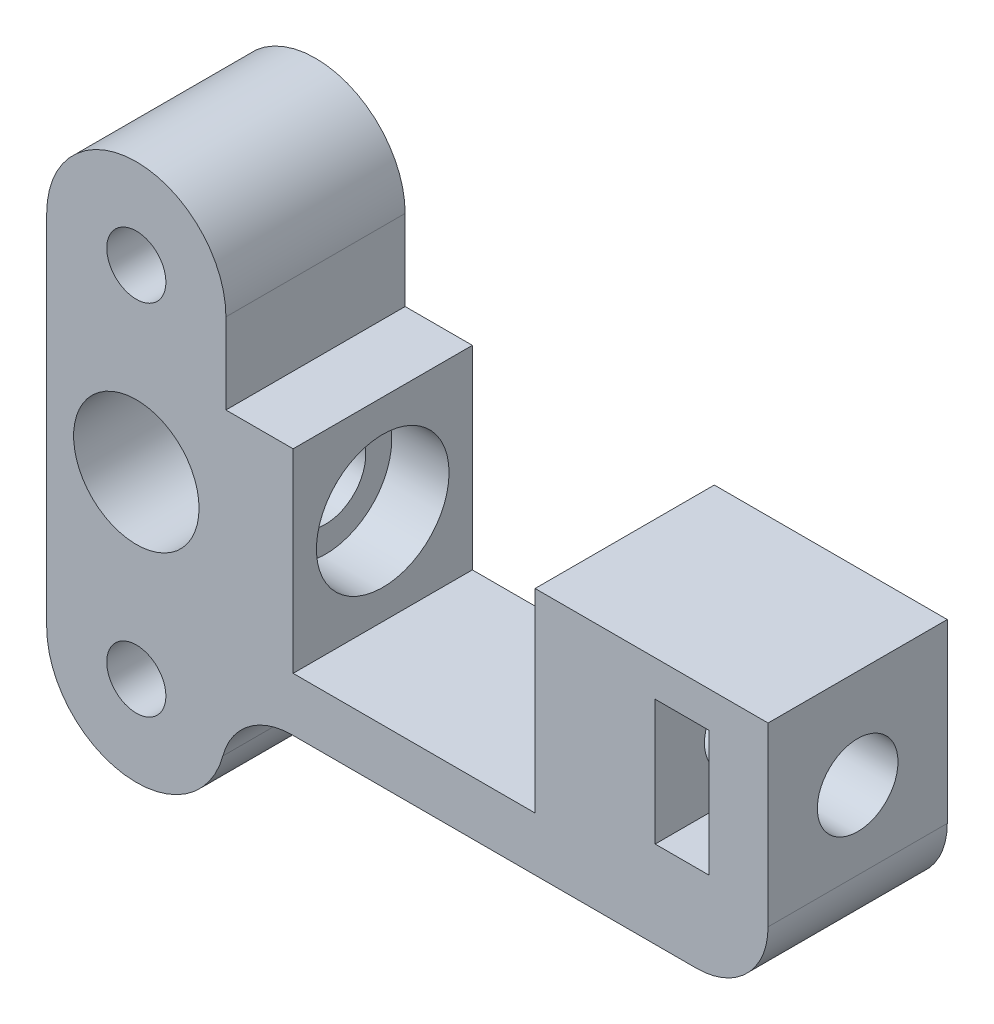
SolidWorks part; units mm, degrees
material "ABS"
ref_plane "Plan de face" through (0, 0, 0) normal (0, 0, 1) x (1, 0, 0)
ref_plane "Plan de dessus" through (0, 0, 0) normal (0, 1, 0) x (1, 0, 0)
ref_plane "Plan de droite" through (0, 0, 0) normal (1, 0, 0) x (0, 0, -1)
sketch "Esquisse1" plane through (0, 0, 0) normal (0, 0, 1) x (1, 0, 0)
  line L0 (0, 0) -> (0, 10) construction
  line L1 (0, 0) -> (0, -10) construction
  line L2 (-5, 10) -> (-5, 2)
  line L3 (-5, 2) -> (-5, -10)
  line L4 (5, 10) -> (5, 0)
  line L5 (5, 0) -> (5, -10)
  circle A0 centre (0, 0) radius 3.5
  circle A1 centre (0, 0) radius 5
  circle A2 centre (0, 10) radius 1.65
  circle A3 centre (0, 10) radius 5
  circle A4 centre (0, -10) radius 1.65
  circle A5 centre (0, -10) radius 5
  point P7 (0, 5)
  point P8 (0, 5)
  dimension "D2" = 3.3
  dimension "D3" = 7
  dimension "D5" = 0
  dimension "D1" = 10
extrude "Shape" add sketch "Esquisse1" along normal blind 10 contours A3 A2 | A3 L2 A1 L4 | A1 A0 | A5 L5 A1 L3 | A5 A4 | A3 A1 L4 | A5 A1 L3
sketch "Esquisse5" plane through (0, 0, 0) normal (0, 0, -1) x (-1, 0, 0)
  circle A0 centre (0, 10) radius 1.65
  circle A1 centre (0, 0) radius 3.5
  circle A2 centre (0, -10) radius 1.65
  circle A3 centre (0, 10) radius 1.65 construction
  circle A4 centre (0, 0) radius 3.5 construction
  circle A5 centre (0, -10) radius 1.65 construction
extrude "HolesCirclesRepeat" [suppressed] cut sketch "Esquisse5" along normal blind 29
sketch "Esquisse6" plane through (5, 0, 0) normal (1, 0, 0) x (0, 0, -1)
  line L0 (0, 0) -> (-10, 0) construction
  line L1 (0, 10) -> (0, -10) construction
  line L2 (-10, 10) -> (-10, -10) construction
  line L4 (0, -7.5) -> (-10, -7.5)
  line L5 (0, -7.5) -> (0, 7.5)
  line L6 (0, 7.5) -> (-10, 7.5)
  line L7 (-10, -7.5) -> (-10, 7.5)
  line L8 (0, -7.5) -> (-10, 7.5) construction
  line L9 (0, 7.5) -> (-10, -7.5) construction
  point P6 (-5, 0)
  dimension "D1" = 15
extrude "MainShape" add sketch "Esquisse6" along normal blind 30.25
sketch "Esquisse10" plane through (0, 0, 0) normal (0, 0, -1) x (-1, 0, 0)
  line L0 (-35.25, 7.5) -> (-5, 7.5) construction
  line L1 (-22.25, 7.5) -> (-8.75, 7.5)
  line L2 (-22.25, 7.5) -> (-22.25, -5.3512)
  line L3 (-22.25, -5.3512) -> (-8.75, -5.3512)
  line L4 (-8.75, 7.5) -> (-8.75, -5.3512)
  line L8 (-5, 10) -> (-5, 7.5) construction
  dimension "D1" = 3.75
  dimension "D2" = 13.5
extrude "SpaceRemover" cut sketch "Esquisse10" against normal blind 13
sketch "Esquisse11" plane through (35.25, 0, 0) normal (1, 0, 0) x (0, 0, -1)
  line L0 (0, 0) -> (-10, 0) construction
  line L1 (-10, 7.5) -> (-10, -7.5) construction
  circle A0 centre (-5, 0) radius 2.25
  dimension "D1" = 4.5
extrude "Axe" cut sketch "Esquisse11" against normal blind 16
sketch "Esquisse12" plane through (8.75, 0, 0) normal (1, 0, 0) x (0, 0, -1)
  circle A0 centre (-5, 0) radius 3.7
  dimension "D1" = 7.4
extrude "BearingBottom" cut sketch "Esquisse12" against normal blind 3.2
sketch "Esquisse14" plane through (22.25, 0, 0) normal (-1, 0, 0) x (0, 0, 1)
  circle A0 centre (5, 0) radius 3.7
  circle A1 centre (5, 0) radius 3.7 construction
extrude "BearingTop" cut sketch "Esquisse14" against normal blind 3.4
sketch "Esquisse15" plane through (5.55, 0, 0) normal (1, 0, 0) x (0, 0, -1)
  circle A0 centre (-5, 0) radius 2.25
  dimension "D1" = 4.5
extrude "AxeEnd" cut sketch "Esquisse15" against normal blind 1
sketch "Esquisse16" plane through (0, 0, 0) normal (0, 0, -1) x (-1, 0, 0)
  line L0 (-35.25, 0) -> (-25.65, 0) construction
  line L1 (-35.25, -7.5) -> (-35.25, 7.5) construction
  line L2 (-25.65, -2.25) -> (-25.65, 2.25) construction
  line L4 (-28.95, -3.5) -> (-31.95, -3.5)
  line L5 (-28.95, -3.5) -> (-28.95, 3.5)
  line L6 (-28.95, 3.5) -> (-31.95, 3.5)
  line L7 (-31.95, -3.5) -> (-31.95, 3.5)
  line L8 (-28.95, -3.5) -> (-31.95, 3.5) construction
  line L9 (-28.95, 3.5) -> (-31.95, -3.5) construction
  point P6 (-30.45, 0)
  dimension "D1" = 7
  dimension "D2" = 3
extrude "AxeLocker" cut sketch "Esquisse16" against normal up to surface (10 mm away) up to face at (11.875, 0.3581, 10)
sketch "Esquisse17" plane through (0, 0, 0) normal (0, 0, -1) x (-1, 0, 0)
  line L1 (-35.25, -7.5) -> (-5, -7.5)
  line L2 (-35.25, -7.5) -> (-35.25, -8.3512)
  line L3 (-35.25, -8.3512) -> (-5, -8.3512)
  line L4 (-5, -7.5) -> (-5, -8.3512)
  line L6 (-22.25, -5.3512) -> (-8.75, -5.3512) construction
  dimension "D1" = 3
extrude "Renforcment" add sketch "Esquisse17" against normal up to surface (10 mm away) up to face at (30.45, 0, 10)
sketch "Esquisse18" plane through (0, 0, 0) normal (0, 0, -1) x (-1, 0, 0)
  line L0 (-35.25, -8.3512) -> (-35.25, 7.5) construction
  line L1 (-5, 7.5) -> (-35.25, 7.5)
  line L2 (-5, 7.5) -> (-5, 5.5)
  line L3 (-5, 5.5) -> (-35.25, 5.5)
  line L4 (-35.25, 7.5) -> (-35.25, 5.5)
  line L5 (-28.95, 3.5) -> (-31.95, 3.5) construction
  dimension "D1" = 2
extrude "MassRemover" cut sketch "Esquisse18" against normal up to surface (10 mm away) up to face at (11.875, 0.2163, 10)
fillet "Congé1" radius 4 2 edges at (35.25, -8.3512, 5) (5, -8.3512, 5)
sketch "Esquisse19" plane through (4.55, 0, 0) normal (1, 0, 0) x (0, 0, -1)
  circle A0 centre (-5, 0) radius 1
  dimension "D1" = 2
extrude "Remover helper" cut sketch "Esquisse19" against normal blind 10
equation "\"entretoiseBearing\"= 1.5mm"
equation "\"length_tibia\"= 206mm"
equation "\"length_femur\"= 117mm"
equation "\"length_coxa\"= 27mm"
equation "\"height\"= 40mm"
equation "\"width\"= 100mm"
equation "\"lever\"= 40mm"
equation "\"depthMagnet\"= 1mm"
equation "\"errorFlat\"= 0.20mm"
equation "\"errorCircle\"= 0.40mm"
equation "\"cuticule\"=1.5mm"
equation "\"cuticule_attach_w\"=10mm"
equation "\"cuticule_attach_h\"=2.5mm"
equation "\"insert_d\" = 3.2mm"
equation "\"insert_l\" = 5mm"
equation "\"D1@Esquisse11\"=3+\"entretoiseBearing\""
equation "\"D1@Esquisse12\"= 7 + 2 * \"errorFlat\""
equation "\"D1@BearingBottom\" = 3 + \"errorFlat\""
equation "\"D1@MainShape\"=13.5 + 1 + 4 * 3"
equation "\"D1@BearingTop\" = 3 + \"errorFlat\" * 2"
equation "\"D1@Esquisse15\"=\"entretoiseBearing\" + 3"
equation "\"errorFlat_tight\"= 0.15mm"
equation "\"errorCircle_tight\" = 0.30mm"
equation "\"D2@Esquisse1\"=3.00mm +\"errorCircle_tight\""
